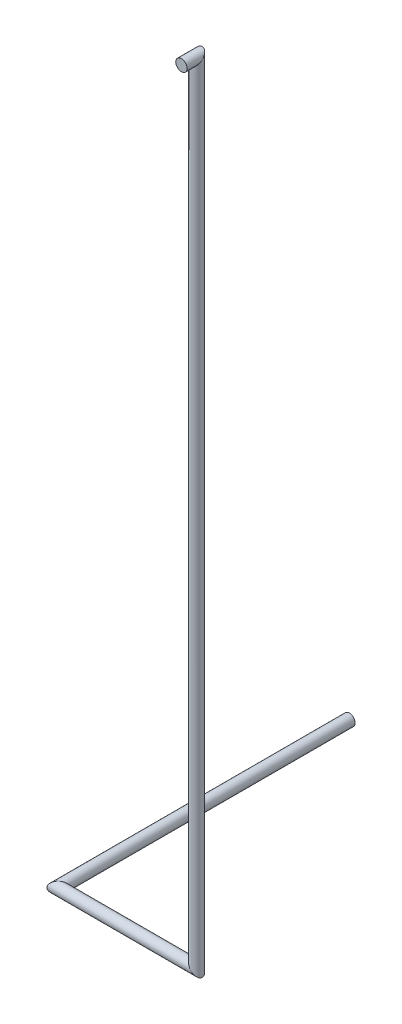
SolidWorks part; units mm, degrees
ref_plane "Plan de face" through (0, 0, 0) normal (0, 0, 1) x (1, 0, 0)
ref_plane "Plan de dessus" through (0, 0, 0) normal (0, 1, 0) x (1, 0, 0)
ref_plane "Plan de droite" through (0, 0, 0) normal (1, 0, 0) x (0, 0, -1)
sketch3d "Esquisse3D2"
  line L0 (0, 0, 0) -> (0, 0, -20)
  line L1 (0, 0, -20) -> (0, -1038, -20)
  line L2 (0, -1038, -20) -> (-182, -1038, -20)
  line L3 (-182, -1038, -20) -> (-182, -1038, -403)
  dimension "D1" = 20
  dimension "D2" = 1038
  dimension "D3" = 182
  dimension "D4" = 383
sketch "Esquisse2" plane through (0, 0, 0) normal (0, 0, 1) x (1, 0, 0)
  circle A0 centre (0, 0) radius 7.5
  dimension "D1" = 15
sweep "Balayage1" add profiles "Esquisse2" path "Esquisse3D2"
